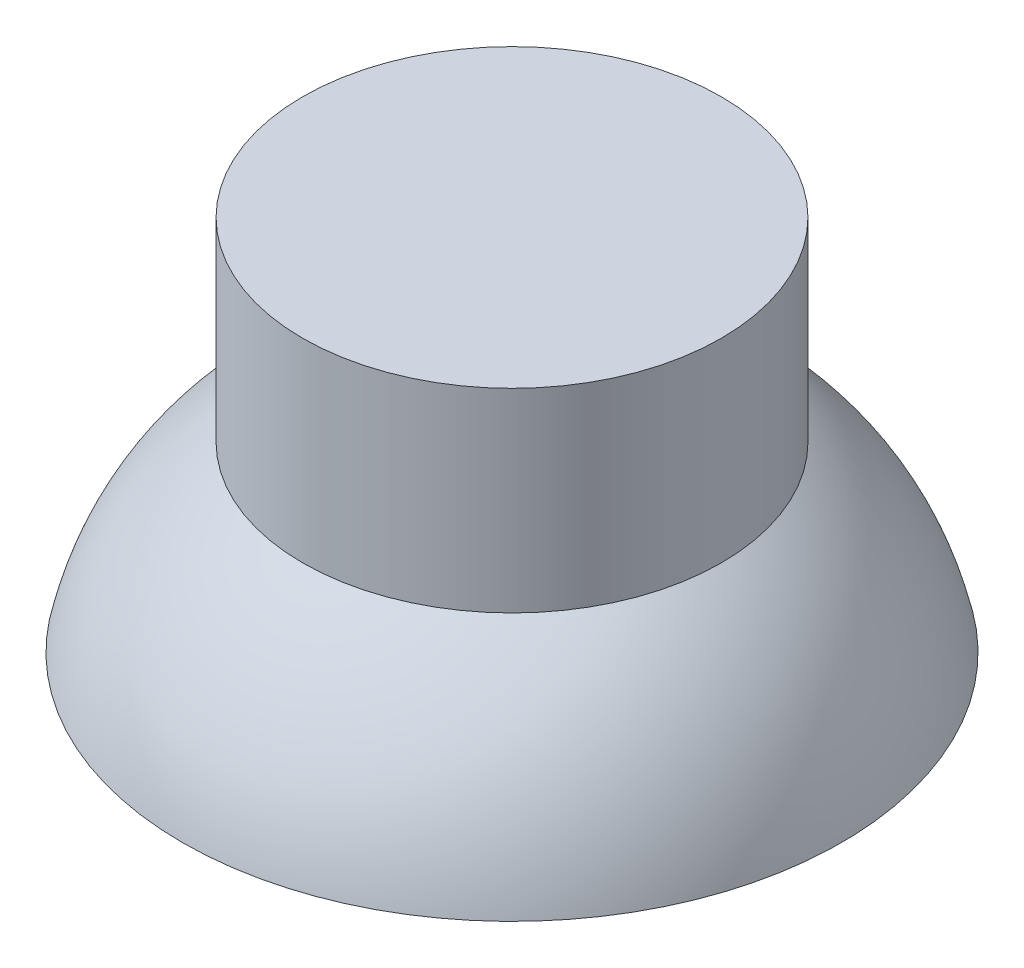
SolidWorks part; units mm, degrees
ref_plane "前视基准面" through (0, 0, 0) normal (0, 0, 1) x (1, 0, 0)
ref_plane "上视基准面" through (0, 0, 0) normal (0, 1, 0) x (1, 0, 0)
ref_plane "右视基准面" through (0, 0, 0) normal (1, 0, 0) x (0, 0, -1)
sketch "草图4" plane through (0, 0, 0) normal (0, 0, 1) x (1, 0, 0)
  line L0 (0, 0) -> (0, -8.2244) construction
  line L1 (-5.25, 1.2321) -> (-4.25, 1.2321)
  line L2 (-4.25, 1.2321) -> (-4.25, -3.1179)
  line L3 (-5.25, 1.2321) -> (-5.25, -2.6482)
  line L4 (-7, -7.2158) -> (-8.2677, -7.2158)
  spline S0 degree 2 poles (-8.2677, -7.2158) (-7.6326, -4.3566) (-5.25, -2.6482) knots 0 0 0 1 1 1
  spline S1 degree 2 poles (-7, -7.2158) (-6.5184, -4.5847) (-4.25, -3.1179) knots 0 0 0 1 1 1
  dimension "D1" = 4.25
  dimension "D2" = 5.25
  dimension "D3" = 4.35
  dimension "D4" = 7
revolve "旋转1" add sketch "草图4" angle 360 about L0
sketch "草图5" plane through (0, 1.2321, 0) normal (0, 1, 0) x (1, 0, 0)
  circle A0 centre (0, 0) radius 5.25 construction
  circle A1 centre (0, 0) radius 5.25
extrude "凸台-拉伸2" add sketch "草图5" along normal blind 1
